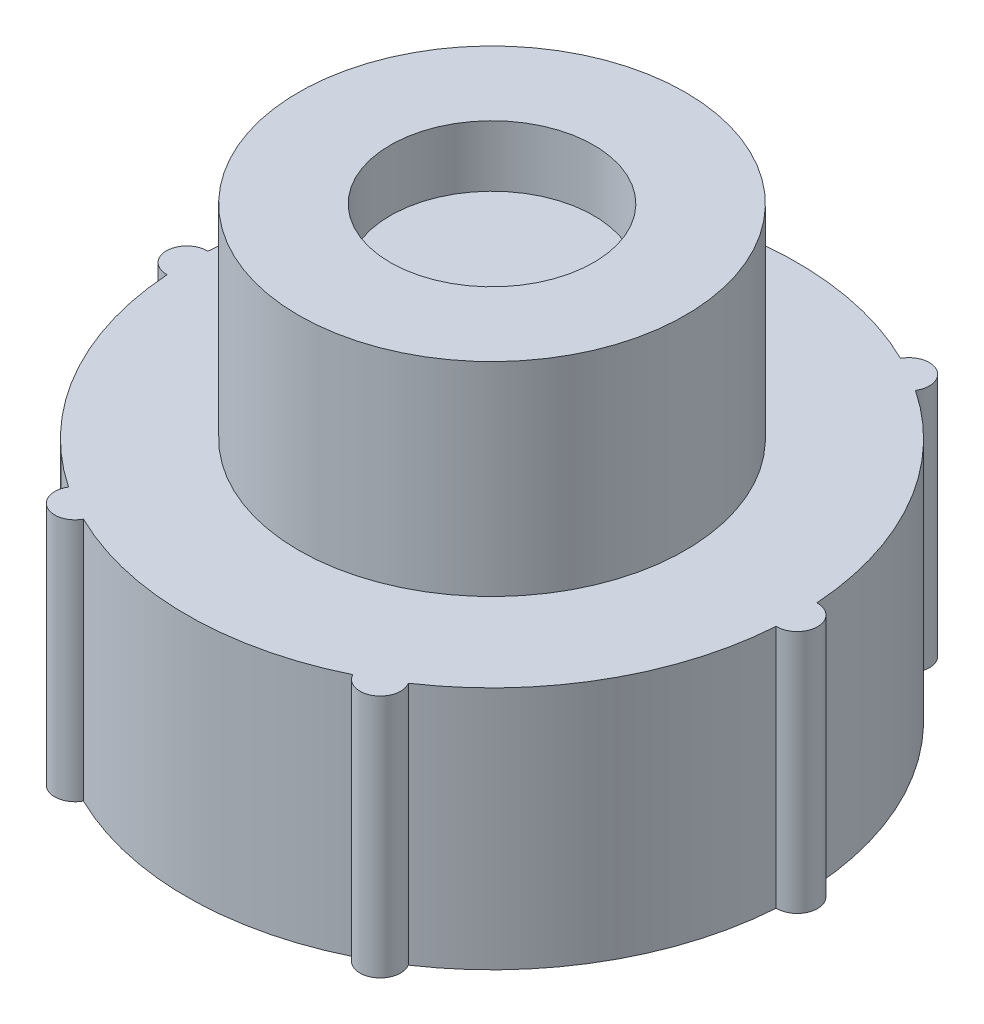
SolidWorks part; units mm, degrees
ref_plane "Front Plane" through (0, 0, 0) normal (0, 0, 1) x (1, 0, 0)
ref_plane "Top Plane" through (0, 0, 0) normal (0, 1, 0) x (1, 0, 0)
ref_plane "Right Plane" through (0, 0, 0) normal (1, 0, 0) x (0, 0, -1)
sketch "Sketch1" plane through (0, 0, 0) normal (0, 1, 0) x (1, 0, 0)
  circle A0 centre (0, 0) radius 15
  dimension "D1" = 30
extrude "Boss-Extrude1" add sketch "Sketch1" along normal blind 12
sketch "Sketch2" plane through (0, 12, 0) normal (0, 1, 0) x (1, 0, 0)
  circle A0 centre (0, 0) radius 9.5
  dimension "D1" = 19
extrude "Boss-Extrude2" add sketch "Sketch2" along normal blind 10
sketch "Sketch3" plane through (0, 22, 0) normal (0, 1, 0) x (1, 0, 0)
  circle A0 centre (0, 0) radius 5
  dimension "D1" = 10
extrude "Cut-Extrude1" cut sketch "Sketch3" against normal blind 3
sketch "Sketch4" plane through (0, 0, 0) normal (0, -1, 0) x (1, 0, 0)
  circle A0 centre (15, 0) radius 1
  circle A1 centre (0, 0) radius 15 construction
  circle A2 centre (7.5, -12.9904) radius 1
  circle A3 centre (-7.5, -12.9904) radius 1
  circle A4 centre (-15, 0) radius 1
  circle A5 centre (-7.5, 12.9904) radius 1
  circle A6 centre (7.5, 12.9904) radius 1
  point P16 (0, 0)
  dimension "D1" = 2
  dimension "D2" = 6
extrude "Boss-Extrude3" add sketch "Sketch4" against normal up to surface (12 mm away) up to face at (0, 12, 9.5)
